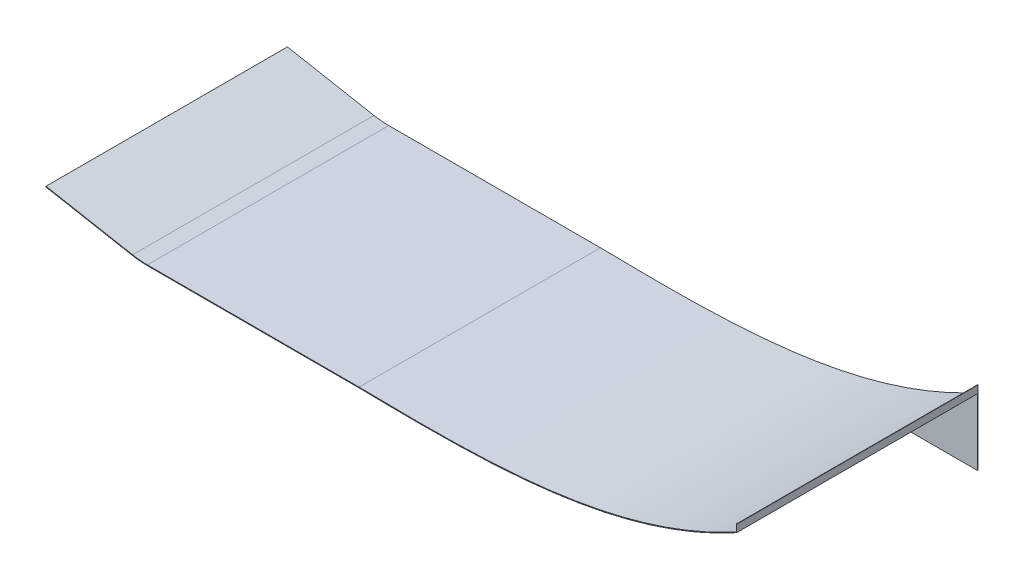
SolidWorks part; units mm, degrees
ref_plane "Front Plane" through (0, 0, 0) normal (0, 0, 1) x (1, 0, 0)
ref_plane "Top Plane" through (0, 0, 0) normal (0, 1, 0) x (1, 0, 0)
ref_plane "Right Plane" through (0, 0, 0) normal (1, 0, 0) x (0, 0, -1)
sketch "Sketch1" plane through (0, 0, 0) normal (0, 0, 1) x (1, 0, 0)
  line L0 (20.2152, 0) -> (595.62, 0)
  line L1 (595.62, 0) -> (1019.98, 11.1123) construction
  line L2 (1019.98, 11.1123) -> (1620.8724, 172.1209) construction
  line L3 (-19.8767, 3.6839) -> (-255.3284, 47.3223)
  line L4 (20.0314, -2) -> (595.6028, -2)
  line L5 (-20.0604, 1.6839) -> (-255.3284, 45.2883)
  line L8 (-0.1838, -2) -> (595.6028, -2) construction
  line L9 (-0.1838, -2) -> (-255.3284, 45.2883) construction
  line L10 (0, 0) -> (595.62, 0) construction
  line L11 (0, 0) -> (-254.9639, 47.2548) construction
  line L15 (1620.8724, 172.1209) -> (1620.8353, 190.368)
  line L18 (-255.3284, 45.2883) -> (-255.3284, 47.3223)
  line L19 (1621.8353, 170.368) -> (1621.8353, 190.368)
  line L20 (1621.8353, 190.368) -> (1620.8353, 190.368)
  arc A0 (20.0314, -2) -> (-20.0604, 1.6839) centre (20.0314, 218) cw
  arc A1 (20.2152, 0) -> (-19.8767, 3.6839) centre (20.2152, 220) cw
  spline S0 degree 3 poles (595.62, 0) (948.0425, -6.0519) (1296.6534, -5.9728) (1620.8724, 172.1209) knots 0 0 0 0 1 1 1 1
  spline S1 degree 1 poles (595.6028, -2) (1621.8353, 170.368) knots 0 0 1 1 construction
  spline S2 degree 3 poles (1621.8353, 170.368) (1616.7748, 167.5882) (1606.5949, 162.09) (1586.2371, 151.4635) (1560.6859, 138.8045) (1529.8964, 124.5993) (1488.6661, 106.925) (1436.8106, 87.1296) (1374.1057, 66.7986) (1310.9545, 49.6388) (1226.1992, 30.6509) (1119.2949, 13.5817) (989.7178, 1.7432) (859.0939, -3.4707) (749.5602, -3.9767) (661.6652, -3.087) (617.6144, -2.378) (595.6028, -2) knots 0.000016 0.000016 0.000016 0.000016 0.015641 0.031266 0.062515 0.093765 0.125014 0.187513 0.250012 0.312511 0.37501 0.500008 0.625006 0.750004 0.875002 0.937501 1 1 1 1
  point P17 (0, 0)
  dimension "D9" = 220
  dimension "D1" = 1039.6
  dimension "D2" = 595.62
  dimension "D3" = 165
  dimension "D4" = 178.5
  dimension "D5" = 1
  dimension "D6" = 169.5
  dimension "D7" = 424.36
  dimension "D10" = 20
  dimension "D8" = 2
extrude "Boss-Extrude4" add sketch "Sketch1" along normal blind 656 contours S0 L15 L20 L19 S2 L4 A0 L5 L18 L3 A1 L0
ref_plane "Plane1" through (0, 0, 131.2) normal (0, 0, 1) x (1, 0, 0)
sketch "Sketch3" plane through (0, 0, 0) normal (0, 0, 1) x (1, 0, 0)
  line L2 (1621.8353, -10) -> (-255.3284, -10)
  line L3 (-255.3284, -10) -> (-255.3284, 45.2883)
  line L4 (1621.8353, 170.368) -> (1621.8353, -10)
  line L5 (20.2152, 0) -> (595.62, 0) construction
  line L6 (595.62, 0) -> (20.2152, 0)
  line L7 (-19.8767, 3.6839) -> (-255.3284, 47.3223)
  line L8 (-255.3284, 47.3223) -> (-255.3284, 45.2883)
  line L9 (-255.3284, 45.2883) -> (-20.0604, 1.6839)
  line L10 (20.0314, -2) -> (595.6028, -2)
  line L15 (-255.3284, 45.2883) -> (-20.0604, 1.6839)
  line L16 (20.0314, -2) -> (595.6028, -2)
  line L22 (1621.8353, 190.368) -> (1620.8353, 190.368)
  line L26 (1621.8353, 170.368) -> (1621.8353, 190.368)
  line L30 (1620.8353, 190.368) -> (1620.8724, 172.1209)
  arc A2 (-19.8767, 3.6839) -> (20.2152, 0) centre (20.2152, 220) ccw
  arc A3 (-20.0604, 1.6839) -> (20.0314, -2) centre (20.0314, 218) ccw
  arc A5 (-20.0604, 1.6839) -> (20.0314, -2) centre (20.0314, 218) ccw
  spline S0 degree 3 poles (-244.9108, -540.0437) (2054.8006, 489.3529) (1825.35, 276.2769) (1586.2371, 151.4635) (1560.6859, 138.8045) (1529.8964, 124.5993) (1488.6661, 106.925) (1436.8106, 87.1296) (1374.1057, 66.7986) (1310.9545, 49.6388) (1226.1992, 30.6509) (1119.2949, 13.5817) (989.7178, 1.7432) (859.0939, -3.4707) (749.5602, -3.9767) (-31.8386, 3.9331) (-798.3831, 85.7785) (-200.1368, -1234.4483) knots -0.671568 -0.671568 -0.671568 -0.671568 0.015641 0.031266 0.062515 0.093765 0.125014 0.187513 0.250012 0.312511 0.37501 0.500008 0.625006 0.750004 0.875002 0.937501 2.972504 2.972504 2.972504 2.972504 only from (1621.8353, 170.368) to (595.6028, -2) construction
  spline S1 degree 3 poles (1621.8353, 170.368) (1616.7748, 167.5882) (1606.5949, 162.09) (1586.2371, 151.4635) (1560.6859, 138.8045) (1529.8964, 124.5993) (1488.6661, 106.925) (1436.8106, 87.1296) (1374.1057, 66.7986) (1310.9545, 49.6388) (1226.1992, 30.6509) (1119.2949, 13.5817) (989.7178, 1.7432) (859.0939, -3.4707) (749.5602, -3.9767) (661.6652, -3.087) (617.6144, -2.378) (595.6028, -2) knots 0.000016 0.000016 0.000016 0.000016 0.015641 0.031266 0.062515 0.093765 0.125014 0.187513 0.250012 0.312511 0.37501 0.500008 0.625006 0.750004 0.875002 0.937501 1 1 1 1
  spline S2 degree 3 poles (2286.4437, 918.4457) (1543.089, -505.6669) (516.246, 253.3108) (-398.0623, -112.1584) knots -0.733042 -0.733042 -0.733042 -0.733042 1.946681 1.946681 1.946681 1.946681 only from (1620.8724, 172.1209) to (595.62, 0)
  spline S3 degree 3 poles (-373.2637, -249.5782) (-231.3562, 35.1253) (242.8562, 1.1524) (749.5602, -3.9767) (859.0939, -3.4707) (989.7178, 1.7432) (1119.2949, 13.5817) (1226.1992, 30.6509) (1310.9545, 49.6388) (1374.1057, 66.7986) (1436.8106, 87.1296) (1488.6661, 106.925) (1529.8964, 124.5993) (1560.6859, 138.8045) (1586.2371, 151.4635) (1789.768, 257.7037) (1983.4886, 425.3789) (670.5717, -137.644) knots -1.191185 -1.191185 -1.191185 -1.191185 0.062515 0.125014 0.250012 0.37501 0.500008 0.625006 0.687505 0.750004 0.812503 0.875002 0.906252 0.937501 0.968751 0.984375 1.562347 1.562347 1.562347 1.562347 only from (595.6028, -2) to (1621.8353, 170.368)
  point P7 (-255.032, 45.2883)
  point P11 (0, 0)
  dimension "D2" = 10
  dimension "D1" = 0
extrude "Boss-Extrude5" add sketch "Sketch3" along normal blind 2
sketch "Sketch7" plane through (0, 0, 131.2) normal (0, 0, 1) x (1, 0, 0)
  line L1 (-19.8767, 3.6839) -> (-255.3284, 47.3223) construction
  line L3 (-19.8767, 3.6839) -> (-255.3284, 47.3223)
  line L4 (-255.3284, 47.3223) -> (-255.3284, 0)
  line L5 (-255.3284, 45.2883) -> (-255.3284, -10) construction
  line L6 (-255.3284, 0) -> (20.2152, 0)
  arc A0 (-19.8767, 3.6839) -> (20.2152, 0) centre (20.2152, 220) ccw construction
  arc A1 (-19.8767, 3.6839) -> (20.2152, 0) centre (20.2152, 220) ccw
extrude "Boss-Extrude9" add sketch "Sketch7" along normal blind 2
pattern_linear "LPattern3" count 4 spacing 131.2 along (0, 0, 1) of "Boss-Extrude9"
